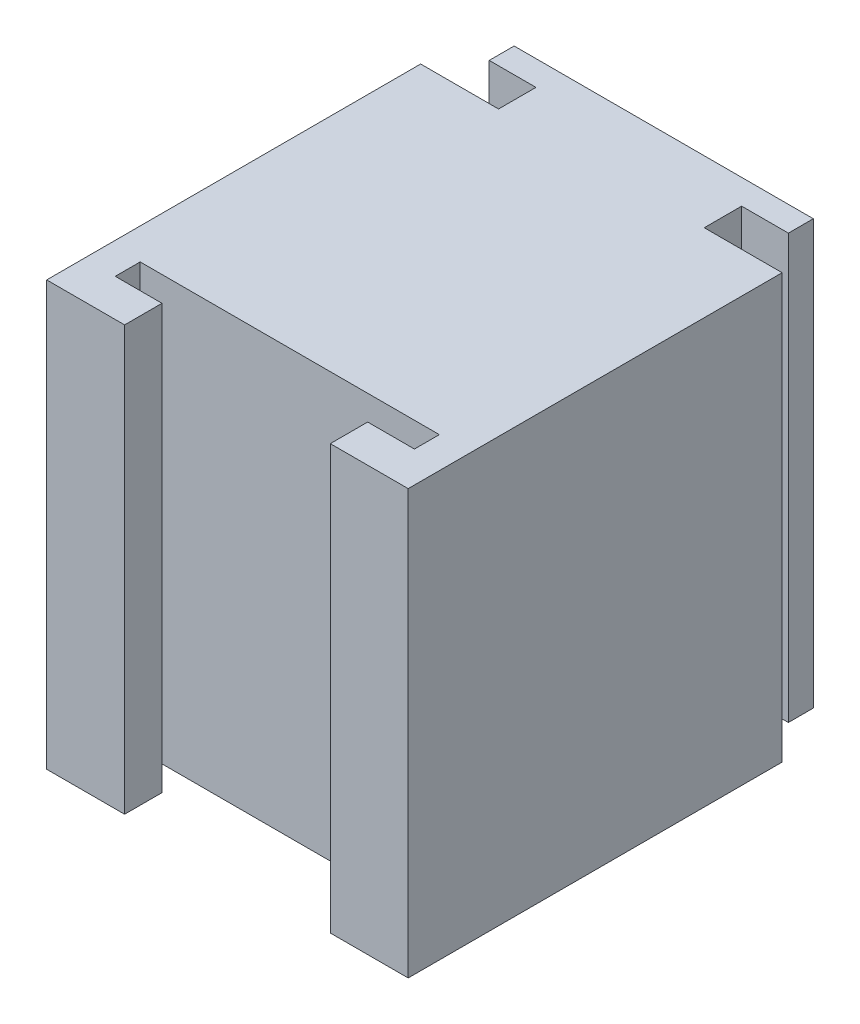
SolidWorks part; units mm, degrees
ref_plane "前视基准面" through (0, 0, 0) normal (0, 0, 1) x (1, 0, 0)
ref_plane "上视基准面" through (0, 0, 0) normal (0, 1, 0) x (1, 0, 0)
ref_plane "右视基准面" through (0, 0, 0) normal (1, 0, 0) x (0, 0, -1)
sketch "Sketch1" plane through (0, 0, 0) normal (0, 1, 0) x (1, 0, 0)
  line L0 (-12, 18) -> (-8.25, 18)
  line L1 (-14.5, 15) -> (-8.25, 15)
  line L2 (-14.5, 15) -> (-14.5, -15)
  line L3 (-14.5, -15) -> (-8.25, -15)
  line L4 (14.5, 15) -> (14.5, -15)
  line L5 (-14.5, 15) -> (14.5, -15) construction
  line L6 (-14.5, -15) -> (14.5, 15) construction
  line L7 (-8.25, 18) -> (-8.25, 15)
  line L8 (-12, 18) -> (-12, 20)
  line L9 (-12, 20) -> (12, 20)
  line L10 (12, 20) -> (12, 18)
  line L11 (12, 18) -> (8.25, 18)
  line L12 (8.25, 18) -> (8.25, 15)
  line L13 (-12, -10) -> (-12, -12)
  line L14 (-12, -12) -> (-8.25, -12)
  line L15 (-8.25, -12) -> (-8.25, -15)
  line L16 (-12, -10) -> (12, -10)
  line L17 (12, -10) -> (12, -12)
  line L18 (12, -12) -> (8.25, -12)
  line L19 (8.25, -12) -> (8.25, -15)
  line L20 (-8.25, 18) -> (8.25, 18) construction
  line L21 (8.25, 15) -> (14.5, 15)
  line L22 (8.25, -15) -> (14.5, -15)
  point P0 (0, 0)
  point P19 (0, 18)
  point P23 (0, 20)
  point P24 (0, -10)
  point P25 (0, 0)
  dimension "D1" = 30
  dimension "D2" = 29
  dimension "D3" = 24
  dimension "D4" = 16.5
  dimension "D5" = 5
  dimension "D6" = 2
  dimension "D7" = 5
  dimension "D8" = 2
extrude "Boss-Extrude1" add sketch "Sketch1" along normal mid plane 34
